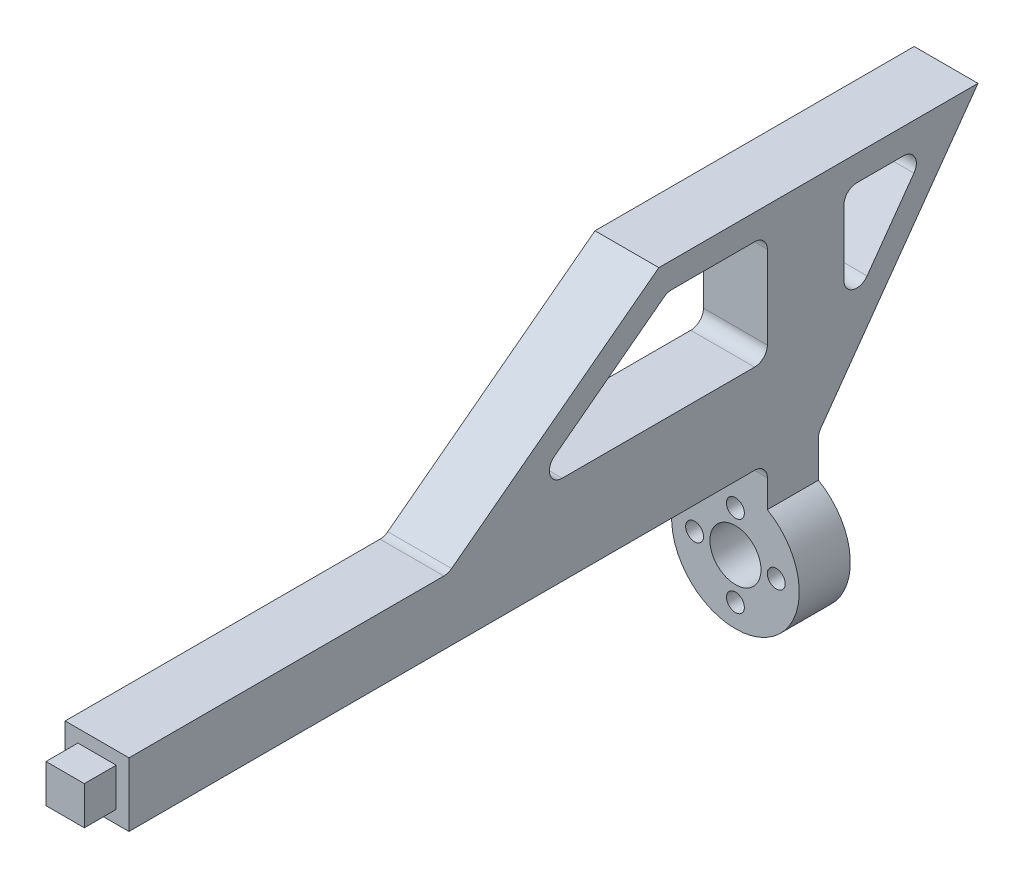
SolidWorks part; units mm, degrees
ref_plane "Front Plane" through (0, 0, 0) normal (0, 0, 1) x (1, 0, 0)
ref_plane "Top Plane" through (0, 0, 0) normal (0, 1, 0) x (1, 0, 0)
ref_plane "Right Plane" through (0, 0, 0) normal (1, 0, 0) x (0, 0, -1)
sketch "Sketch1" plane through (0, 0, 0) normal (0, 0, 1) x (1, 0, 0)
  line L0 (0, 0) -> (0, 127) construction
  line L1 (-6.35, 12.7) -> (-6.35, 10.9985)
  line L3 (6.35, 12.7) -> (6.35, 10.9985)
  line L5 (-6.35, 12.7) -> (-6.35, 63.5)
  line L6 (-6.35, 63.5) -> (6.35, 63.5)
  line L7 (6.35, 12.7) -> (6.35, 63.5)
  circle A0 centre (0, 0) radius 5.08
  arc A1 (-6.35, 10.9985) -> (6.35, 10.9985) centre (0, 0) ccw
  circle A2 centre (0, 8.128) radius 1.778
  circle A3 centre (8.128, 0) radius 1.778
  circle A4 centre (0, -8.128) radius 1.778
  circle A5 centre (-8.128, 0) radius 1.778
  point P15 (0, 0)
  dimension "D1" = 10.16
  dimension "D2" = 25.4
  dimension "D4" = 3.556
  dimension "D3" = 8.128
  dimension "D6" = 12.7
  dimension "D7" = 50.8
  dimension "D8" = 1.7015
  dimension "D5" = 4
extrude "Boss-Extrude1" add sketch "Sketch1" along normal blind 10.16
sketch "Sketch3" plane through (0, 0, 10.16) normal (0, 0, 1) x (1, 0, 0)
  line L0 (0, 0) -> (0, 25.4) construction
  line L2 (-6.35, 19.05) -> (6.35, 19.05)
  line L3 (-6.35, 19.05) -> (-6.35, 31.75)
  line L4 (-6.35, 31.75) -> (6.35, 31.75)
  line L5 (6.35, 19.05) -> (6.35, 31.75)
  line L6 (-6.35, 19.05) -> (6.35, 31.75) construction
  line L7 (-6.35, 31.75) -> (6.35, 19.05) construction
  dimension "D1" = 12.7
  dimension "D2" = 12.7
  dimension "D3" = 25.4
extrude "Boss-Extrude2" add sketch "Sketch3" along normal blind 127
sketch "Sketch5" plane through (-6.35, 0, 0) normal (-1, 0, 0) x (0, 0, 1)
  line L5 (10.16, 63.5) -> (31.75, 63.5)
  line L6 (31.75, 63.5) -> (73.66, 31.75)
  line L7 (10.16, 31.75) -> (73.66, 31.75)
  line L8 (30.043, 58.42) -> (10.16, 58.42)
  line L9 (10.16, 36.83) -> (58.5418, 36.83)
  line L10 (58.5418, 36.83) -> (30.043, 58.42)
  line L11 (10.16, 63.5) -> (10.16, 58.42)
  line L12 (10.16, 36.83) -> (10.16, 31.75)
  dimension "D1" = 21.59
  dimension "D2" = 5.08
  dimension "D3" = 5.08
  dimension "D4" = 5.08
sketch "Sketch6" plane through (0, 0, 137.16) normal (0, 0, 1) x (1, 0, 0)
  line L0 (-6.35, 19.05) -> (6.35, 19.05) construction
  line L1 (-3.81, 21.59) -> (3.81, 21.59)
  line L2 (-3.81, 21.59) -> (-3.81, 29.21)
  line L3 (-3.81, 29.21) -> (3.81, 29.21)
  line L4 (3.81, 21.59) -> (3.81, 29.21)
  line L5 (-3.81, 21.59) -> (3.81, 29.21) construction
  line L6 (-3.81, 29.21) -> (3.81, 21.59) construction
  line L7 (-6.35, 31.75) -> (-6.35, 19.05) construction
  point P0 (0, 25.4)
  point P5 (0, 25.4)
  point P6 (0, 0)
  point P11 (0.3578, 26.256)
  point P12 (0, 0)
  dimension "D1" = 7.62
  dimension "D2" = 7.62
  dimension "D3" = 6.35
  dimension "D4" = 6.35
extrude "Boss-Extrude3" add sketch "Sketch6" along normal blind 6.35
extrude "Boss-Extrude4" add sketch "Sketch5" along normal up to surface (12.7 mm away) from surface at -12.7 up to face at (-6.35, 31.3246, 39.37) starting at face at (6.35, 31.3246, 39.37)
fillet "Fillet2" radius 2.54 1 edges at (0, 31.75, 73.66)
sketch "Sketch7" plane through (6.35, 0, 0) normal (1, 0, 0) x (0, 0, -1)
  line L0 (0, 63.5) -> (0, 19.05)
  line L1 (0, 10.9985) -> (0, 63.5) construction
  line L2 (0, 63.5) -> (31.75, 63.5)
  line L3 (31.75, 63.5) -> (0, 19.05)
  line L4 (5.08, 58.42) -> (21.8786, 58.42)
  line L5 (5.08, 58.42) -> (5.08, 34.902)
  line L7 (5.08, 34.902) -> (21.8786, 58.42)
  dimension "D1" = 44.45
  dimension "D2" = 31.75
  dimension "D3" = 5.08
  dimension "D4" = 5.08
extrude "Boss-Extrude5" add sketch "Sketch7" along direction (-1, 0, 0) on the side of the normal up to surface (12.7 mm away) from surface at -12.7 starting at face at (-6.35, 47.625, 27.2262)
fillet "Fillet3" radius 2.54 9 edges at (0, 19.05, 0) (0, 34.902, -5.08) (0, 58.42, -5.08) (0, 58.42, -21.8786) (0, 58.42, 10.16) (0, 19.05, 10.16) (0, 36.83, 10.16) (0, 58.42, 30.043) (0, 36.83, 58.5418)
